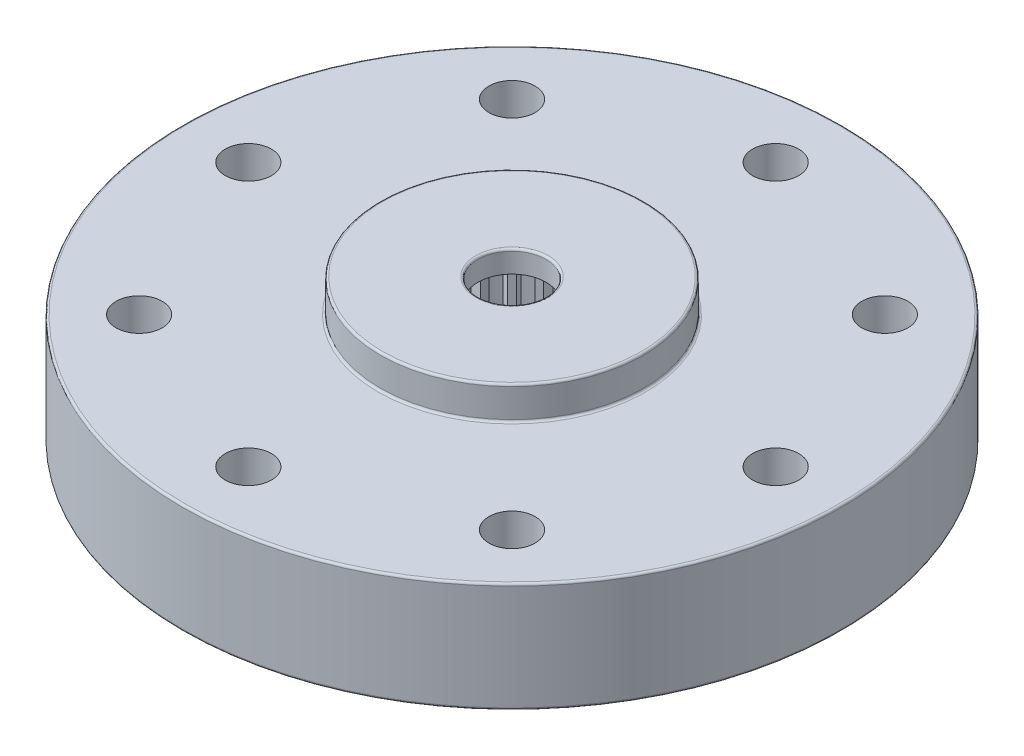
SolidWorks part; units mm, degrees
ref_plane "Plan de face" through (0, 0, 0) normal (0, 0, 1) x (1, 0, 0)
ref_plane "Plan de dessus" through (0, 0, 0) normal (0, 1, 0) x (1, 0, 0)
ref_plane "Plan de droite" through (0, 0, 0) normal (1, 0, 0) x (0, 0, -1)
sketch "Esquisse2" plane through (0, 0, 0) normal (0, 1, 0) x (1, 0, 0)
  circle A0 centre (0, 0) radius 15
  circle A1 centre (0, 0) radius 1.55
  dimension "D1" = 30
  dimension "D2" = 3.1
extrude "Boss.-Extru.1" add sketch "Esquisse2" along normal blind 6.5
sketch "Esquisse3" plane through (0, 6.5, 0) normal (0, 1, 0) x (1, 0, 0)
  circle A0 centre (0, 0) radius 6
  circle A1 centre (0, 0) radius 15
  circle A2 centre (0, 0) radius 15 construction
  dimension "D1" = 12
extrude "Enlèv. mat.-Extru.1" cut sketch "Esquisse3" against normal blind 1.5
fillet "Congé1" radius 0.1 5 edges at (0, 0, 15) (0, 5, 15) (0, 5, 6) (0, 6.5, 6) (0, 6.5, 1.55)
sketch "Esquisse4" plane through (0, 0, 0) normal (0, -1, 0) x (1, 0, 0)
  circle A0 centre (0, 12) radius 1.05
  dimension "D1" = 2.1
  dimension "D2" = 12
extrude "Enlèv. mat.-Extru.2" cut sketch "Esquisse4" against normal blind 5
pattern_circular "Répétition circulaire1" count 8 over 360 about axis through (0, 0, 0) along (0, 1, 0) of "Enlèv. mat.-Extru.2"
sketch "Esquisse5" plane through (0, 0, 0) normal (0, -1, 0) x (1, 0, 0)
  circle A0 centre (0, 0) radius 4
  dimension "D1" = 8
extrude "Enlèv. mat.-Extru.3" cut sketch "Esquisse5" against normal blind 5.5
sketch "Esquisse6" plane through (0, 0, 0) normal (0, -1, 0) x (1, 0, 0)
  line L0 (0, 0) -> (0, 10.3519) construction
  line L1 (0, 0) -> (8.7625, 0) construction
  line L2 (1.1, 8.7062) -> (1.1, 6.4062)
  line L3 (6.4062, 1.1) -> (8.7062, 1.1)
  arc A0 (1.1, 6.4062) -> (6.4062, 1.1) centre (0, 0) cw
  arc A1 (1.1, 8.7062) -> (8.7062, 1.1) centre (0, 0) cw
  dimension "D3" = 6.5
  dimension "D1" = 2.2
  dimension "D2" = 1.1
  dimension "D4" = 2.3
extrude "Enlèv. mat.-Extru.4" cut sketch "Esquisse6" against normal blind 2.5
fillet "Congé2" radius 0.25 4 edges at (8.7062, 1.25, 1.1) (6.4062, 1.25, 1.1) (1.1, 1.25, 6.4062) (1.1, 1.25, 8.7062)
pattern_circular "Répétition circulaire2" count 4 over 360 about axis through (0, 0, 0) along (0, 1, 0) of "Enlèv. mat.-Extru.4", "Congé2"
sketch "Esquisse7" plane through (0, 0, 0) normal (0, -1, 0) x (1, 0, 0)
  line L0 (0, 0) -> (0, 5.3406) construction
  line L1 (0, 5.3406) -> (-2.3501, 4) construction
  line L2 (-2.3501, 4) -> (2.3948, 4) construction
  line L5 (0.3, 4) -> (-0.3, 4)
  line L6 (-0.3, 4) -> (-0.1392, 3.4)
  line L7 (-0.1392, 3.4) -> (0.1392, 3.4)
  line L8 (0.1392, 3.4) -> (0.3, 4)
  circle A0 centre (0, 0) radius 4 construction
  dimension "D1" = 0.6
  dimension "D2" = 15
  dimension "D3" = 0.6
extrude "Boss.-Extru.2" add sketch "Esquisse7" against normal up to surface (5.5 mm away) up to face at (0, 5.5, -1.55)
pattern_circular "Répétition circulaire3" count 24 over 360 about axis through (0, 0, 0) along (0, 1, 0) of "Boss.-Extru.2"
